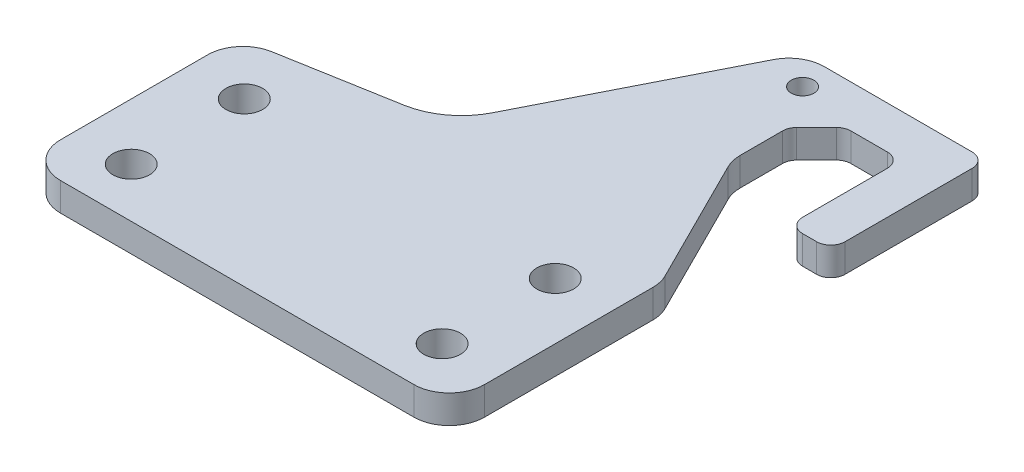
SolidWorks part; units mm, degrees
material "Thornel Mat VMA"
ref_plane "Front" through (0, 0, 0) normal (0, 0, 1) x (1, 0, 0)
ref_plane "Top" through (0, 0, 0) normal (0, 1, 0) x (1, 0, 0)
ref_plane "Right" through (0, 0, 0) normal (1, 0, 0) x (0, 0, -1)
sketch "草图1" plane through (0, 0, 0) normal (0, 1, 0) x (1, 0, 0)
  line L0 (0, 0) -> (0, 59.5856) construction
  line L1 (-30, -15) -> (30, -15)
  line L2 (-30, -15) -> (-30, 15)
  line L4 (30, -15) -> (30, 15)
  line L5 (-30, -15) -> (30, 15) construction
  line L6 (-30, 15) -> (30, -15) construction
  line L7 (30, 15) -> (20, 35)
  line L8 (20, 35) -> (20, 43)
  line L9 (20, 43) -> (24, 47)
  line L10 (24, 47) -> (24, 53)
  line L11 (24, 53) -> (12, 53)
  line L13 (12, 53) -> (-5, 19.4082)
  line L14 (-5, 19.4082) -> (-30, 15)
  point P0 (0, 0)
  dimension "D1" = 30
  dimension "D2" = 60
  dimension "D3" = 20
  dimension "D4" = 8
  dimension "D5" = 8
  dimension "D6" = 4
  dimension "D7" = 135
  dimension "D8" = 20
  dimension "D9" = 6
  dimension "D10" = 100
  dimension "D11" = 25
extrude "凸台-拉伸1" add sketch "草图1" along normal blind 4
fillet "圆角1" radius 10 1 edges at (-5, 2, -19.4082)
fillet "圆角2" radius 5 6 edges at (12, 2, -53) (20, 2, -35) (30, 2, -15) (30, 2, 15) (-30, 2, 15) (-30, 2, -15)
sketch "草图2" plane through (0, 4, 0) normal (0, 1, 0) x (1, 0, 0)
  line L0 (-30, 10.8045) -> (-30, -10) construction
  line L1 (-25, -15) -> (25, -15) construction
  line L2 (0, 0) -> (0, 22.3735) construction
  line L4 (0, 0) -> (-17.4119, 0) construction
  circle A0 centre (-22, 8) radius 2.6
  circle A1 centre (22, 8) radius 2.6
  circle A2 centre (22, -8) radius 2.6
  circle A3 centre (-22, -8) radius 2.6
  dimension "D1" = 5.2
  dimension "D2" = 8
  dimension "D3" = 23
extrude "切除-拉伸1" cut sketch "草图2" against normal through all
sketch "草图3" plane through (0, 0, 0) normal (0, -1, 0) x (1, 0, 0)
  line L0 (24, -53) -> (15.0734, -53) construction
  line L1 (20, -36.1803) -> (20, -43) construction
  circle A0 centre (16, -49) radius 1.6
  dimension "D1" = 3.2
  dimension "D2" = 4
  dimension "D3" = 4
extrude "切除-拉伸2" cut sketch "草图3" against normal through all
sketch "草图4" plane through (0, 4, 0) normal (0, 1, 0) x (1, 0, 0)
  line L0 (24, 47) -> (32, 47)
  line L1 (32, 47) -> (32, 31)
  line L2 (32, 31) -> (38, 31)
  line L3 (38, 31) -> (38, 53)
  line L4 (38, 53) -> (24, 53)
  line L5 (24, 53) -> (24, 47)
  point P4 (35.9007, 49)
  dimension "D1" = 14
  dimension "D2" = 6
  dimension "D3" = 22
extrude "凸台-拉伸2" add sketch "草图4" against normal blind 4
fillet "圆角3" radius 2 6 edges at (20, 2, -43) (24, 2, -47) (32, 2, -47) (32, 2, -31) (38, 2, -53) (38, 2, -31)
